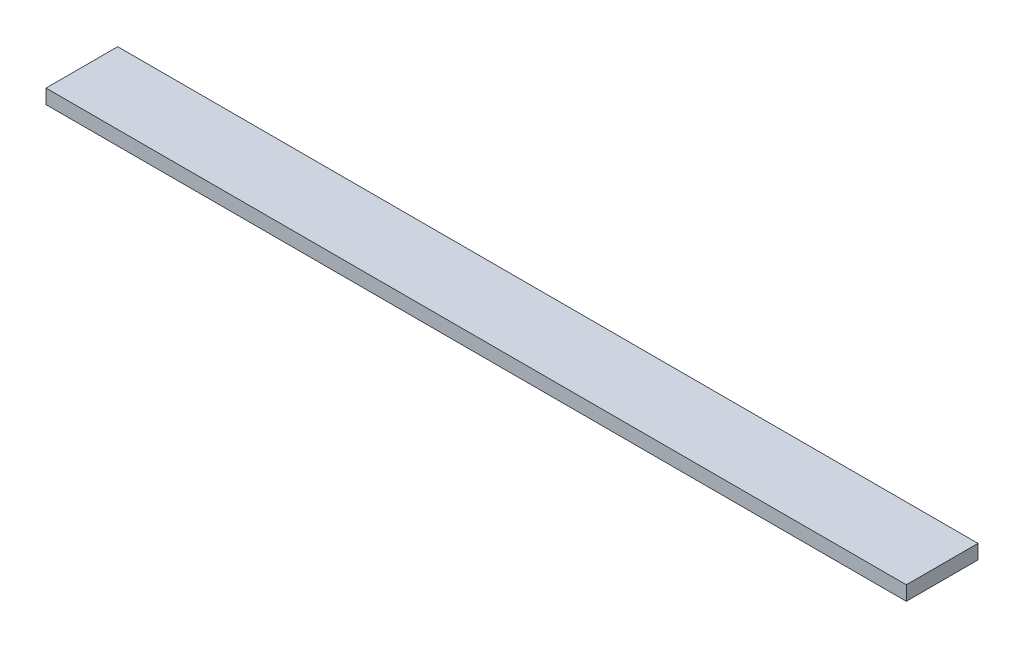
SolidWorks part; units mm, degrees
ref_plane "Front Plane" through (0, 0, 0) normal (0, 0, 1) x (1, 0, 0)
ref_plane "Top Plane" through (0, 0, 0) normal (0, 1, 0) x (1, 0, 0)
ref_plane "Right Plane" through (0, 0, 0) normal (1, 0, 0) x (0, 0, -1)
sketch "Sketch1" plane through (0, 0, 0) normal (0, 1, 0) x (1, 0, 0)
  line L1 (-152.4, -12.7) -> (152.4, -12.7)
  line L2 (-152.4, -12.7) -> (-152.4, 12.7)
  line L3 (-152.4, 12.7) -> (152.4, 12.7)
  line L4 (152.4, -12.7) -> (152.4, 12.7)
  line L5 (-152.4, -12.7) -> (152.4, 12.7) construction
  line L6 (-152.4, 12.7) -> (152.4, -12.7) construction
  point P0 (0, 0)
  dimension "D1" = 304.8
  dimension "D2" = 25.4
extrude "Boss-Extrude1" add sketch "Sketch1" along normal blind 5.08
